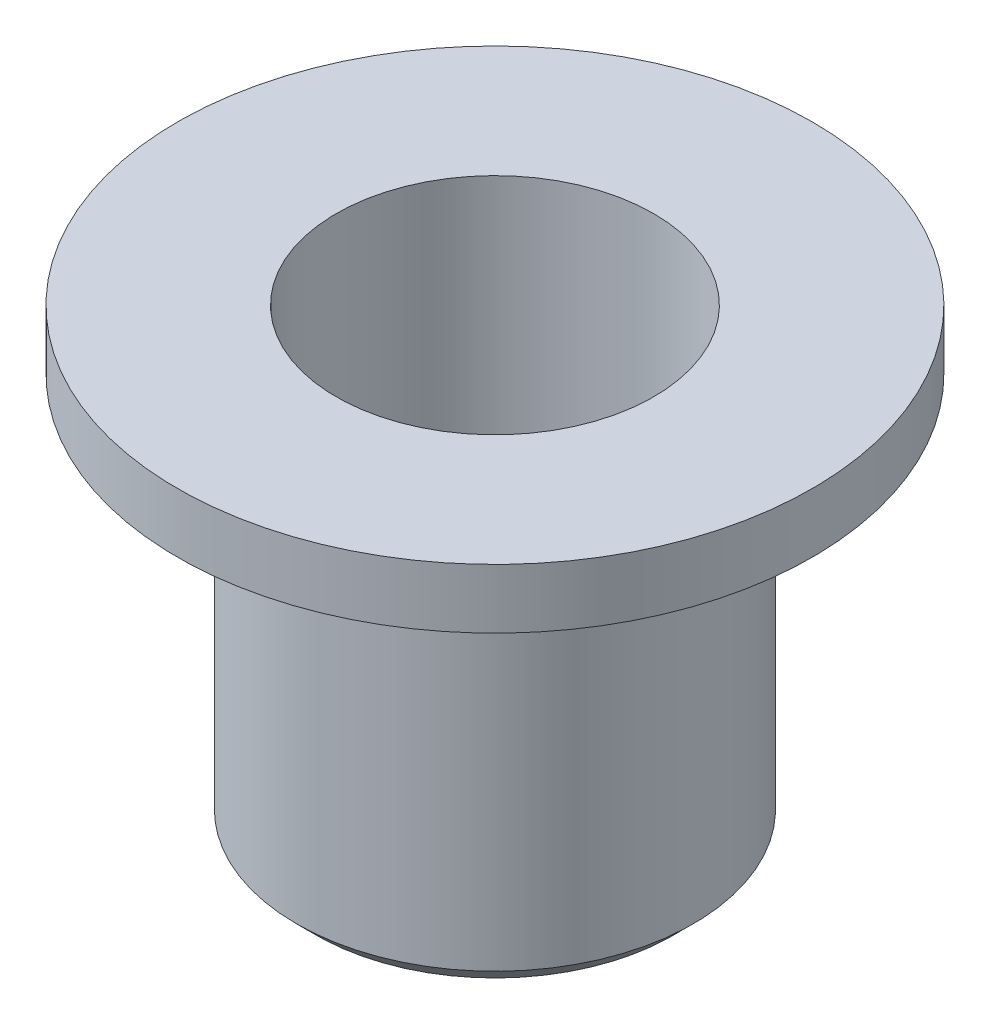
SolidWorks part; units mm, degrees
ref_plane "Plan1" through (0, 0, 0) normal (0, 0, 1) x (1, 0, 0)
ref_plane "Plan2" through (0, 0, 0) normal (0, 1, 0) x (1, 0, 0)
ref_plane "Plan3" through (0, 0, 0) normal (1, 0, 0) x (0, 0, -1)
sketch "Esquisse1" plane through (0, 0, 0) normal (0, 0, 1) x (1, 0, 0)
  line L0 (0, 0) -> (0, 100) construction
  line L1 (4, 0) -> (4.5, 0)
  line L2 (5, 0.5) -> (5, 10)
  line L3 (5, 10) -> (8, 10)
  line L4 (8, 10) -> (8, 11.5)
  line L5 (8, 11.5) -> (4, 11.5)
  line L6 (4, 11.5) -> (4, 0)
  line L7 (4.5, 0) -> (5, 0.5)
  point P4 (5, 0)
  dimension "D1" = 8
  dimension "D2" = 10
  dimension "D3" = 16
  dimension "D4" = 1.5
  dimension "D5" = 10
  dimension "D8" = 0.5
revolve "Base-Révolution" add sketch "Esquisse1" angle 360 about L0
